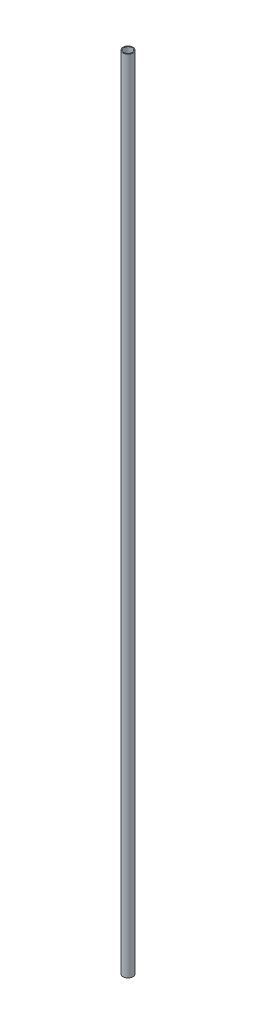
SolidWorks part; units mm, degrees
material "Hexcel AS4C (3000 Filaments)"
ref_plane "Front Plane" through (0, 0, 0) normal (0, 0, 1) x (1, 0, 0)
ref_plane "Top Plane" through (0, 0, 0) normal (0, 1, 0) x (1, 0, 0)
ref_plane "Right Plane" through (0, 0, 0) normal (1, 0, 0) x (0, 0, -1)
sketch "Sketch1" plane through (0, 0, 0) normal (0, 1, 0) x (1, 0, 0)
  circle A0 centre (0, 0) radius 3
  circle A1 centre (0, 0) radius 2.5
  dimension "D1" = 6
  dimension "D2" = 5
extrude "Boss-Extrude1" add sketch "Sketch1" along normal blind 480
